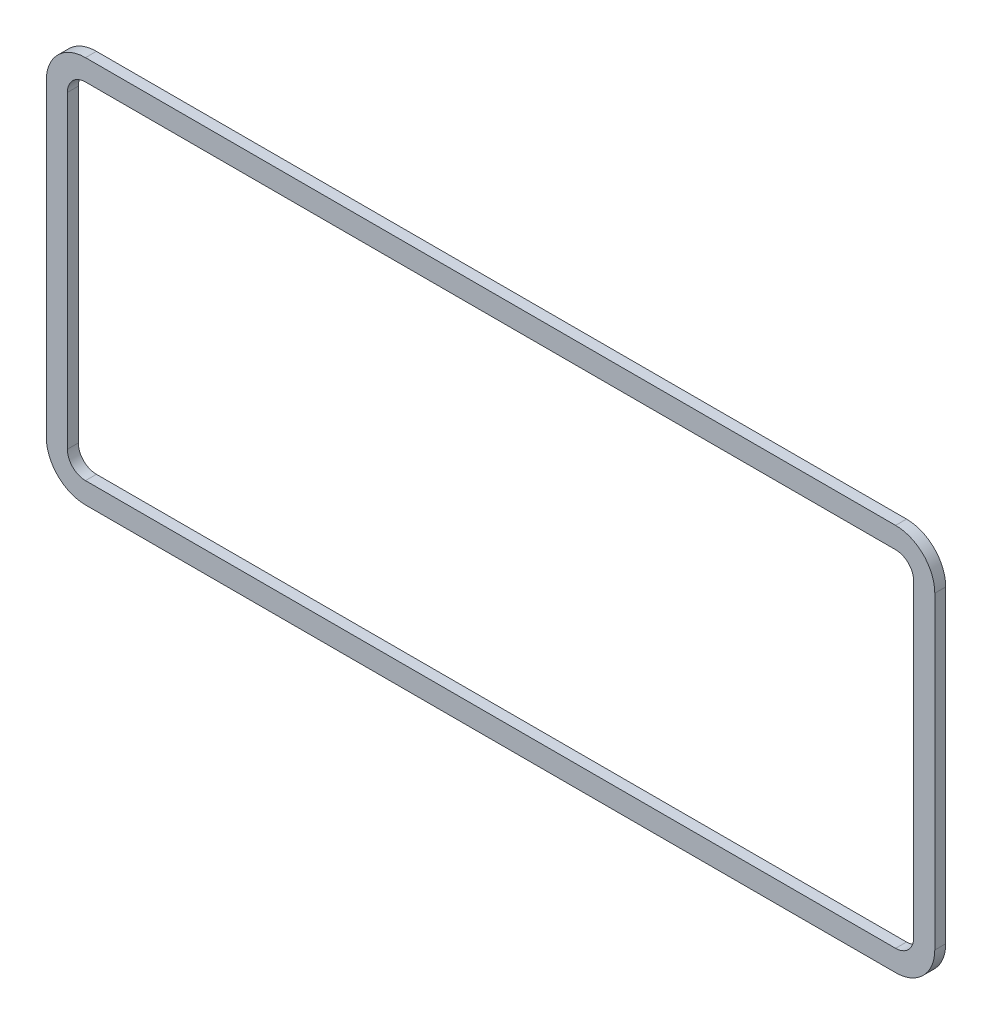
SolidWorks part; units mm, degrees
ref_plane "Front Plane" through (0, 0, 0) normal (0, 0, 1) x (1, 0, 0)
ref_plane "Top Plane" through (0, 0, 0) normal (0, 1, 0) x (1, 0, 0)
ref_plane "Right Plane" through (0, 0, 0) normal (1, 0, 0) x (0, 0, -1)
sketch "Sketch1" plane through (0, 0, 0) normal (0, 0, 1) x (1, 0, 0)
  line L0 (-73.914, -31.496) -> (73.914, -31.496) construction
  line L1 (77.216, -28.194) -> (77.216, 28.194) construction
  line L2 (73.914, 31.496) -> (-73.914, 31.496) construction
  line L3 (-77.216, 28.194) -> (-77.216, -28.194) construction
  line L4 (-73.914, -35.3441) -> (73.914, -35.3441)
  line L5 (81.0641, -28.194) -> (81.0641, 28.194)
  line L6 (73.914, 35.3441) -> (-73.914, 35.3441)
  line L7 (-81.0641, 28.194) -> (-81.0641, -28.194)
  line L8 (-73.914, -35.3441) -> (73.914, -35.3441)
  line L9 (81.0641, -28.194) -> (81.0641, 28.194)
  line L10 (73.914, 35.3441) -> (-73.914, 35.3441)
  line L11 (-81.0641, 28.194) -> (-81.0641, -28.194)
  line L12 (-73.914, -31.496) -> (73.914, -31.496)
  line L13 (77.216, -28.194) -> (77.216, 28.194)
  line L14 (73.914, 31.496) -> (-73.914, 31.496)
  line L15 (-77.216, 28.194) -> (-77.216, -28.194)
  arc A0 (-77.216, -28.194) -> (-73.914, -31.496) centre (-73.914, -28.194) ccw construction
  arc A1 (73.914, -31.496) -> (77.216, -28.194) centre (73.914, -28.194) ccw construction
  arc A2 (77.216, 28.194) -> (73.914, 31.496) centre (73.914, 28.194) ccw construction
  arc A3 (-73.914, 31.496) -> (-77.216, 28.194) centre (-73.914, 28.194) ccw construction
  arc A4 (-81.0641, -28.194) -> (-73.914, -35.3441) centre (-73.914, -28.194) ccw
  arc A5 (73.914, -35.3441) -> (81.0641, -28.194) centre (73.914, -28.194) ccw
  arc A6 (81.0641, 28.194) -> (73.914, 35.3441) centre (73.914, 28.194) ccw
  arc A7 (-73.914, 35.3441) -> (-81.0641, 28.194) centre (-73.914, 28.194) ccw
  arc A8 (-81.0641, -28.194) -> (-73.914, -35.3441) centre (-73.914, -28.194) ccw
  arc A9 (73.914, -35.3441) -> (81.0641, -28.194) centre (73.914, -28.194) ccw
  arc A10 (81.0641, 28.194) -> (73.914, 35.3441) centre (73.914, 28.194) ccw
  arc A11 (-73.914, 35.3441) -> (-81.0641, 28.194) centre (-73.914, 28.194) ccw
  arc A12 (-77.216, -28.194) -> (-73.914, -31.496) centre (-73.914, -28.194) ccw
  arc A13 (73.914, -31.496) -> (77.216, -28.194) centre (73.914, -28.194) ccw
  arc A14 (77.216, 28.194) -> (73.914, 31.496) centre (73.914, 28.194) ccw
  arc A15 (-73.914, 31.496) -> (-77.216, 28.194) centre (-73.914, 28.194) ccw
  dimension "D1" = 0
extrude "Boss-Extrude1" add sketch "Sketch1" along normal up to surface (1.9939 mm away)
